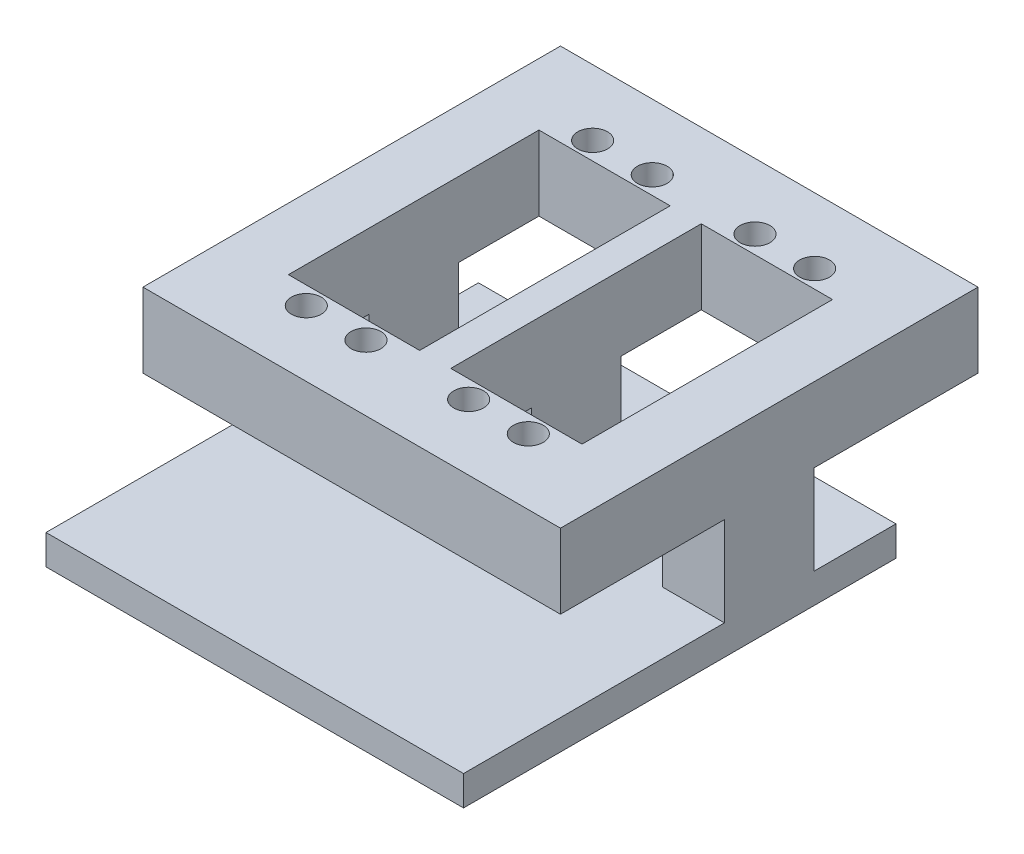
SolidWorks part; units mm, degrees
ref_plane "Front Plane" through (0, 0, 0) normal (0, 0, 1) x (1, 0, 0)
ref_plane "Top Plane" through (0, 0, 0) normal (0, 1, 0) x (1, 0, 0)
ref_plane "Right Plane" through (0, 0, 0) normal (1, 0, 0) x (0, 0, -1)
sketch "Sketch1" plane through (0, 0, 0) normal (0, 1, 0) x (1, 0, 0)
  line L0 (0, 74.7873) -> (0, -69.1899) construction
  line L1 (-35, 35) -> (35, 35)
  line L2 (-35, 35) -> (-35, -35)
  line L3 (-35, -35) -> (35, -35)
  line L4 (35, 35) -> (35, -35)
  line L5 (-35, 35) -> (35, -35) construction
  line L6 (-35, -35) -> (35, 35) construction
  line L7 (-24.6085, 21) -> (-2.6085, 21)
  line L8 (-24.6085, 21) -> (-24.6085, -21)
  line L9 (-24.6085, -21) -> (-2.6085, -21)
  line L10 (-2.6085, 21) -> (-2.6085, -21)
  line L11 (-24.6085, 21) -> (-2.6085, -21) construction
  line L12 (-24.6085, -21) -> (-2.6085, 21) construction
  line L13 (-120.0494, 0) -> (109.3545, 0) construction
  line L14 (35, 35) -> (-35, -35) construction
  line L15 (24.6085, -21) -> (2.6085, -21)
  line L16 (2.6085, 21) -> (2.6085, -21)
  line L17 (24.6085, 21) -> (2.6085, 21)
  line L18 (24.6085, 21) -> (24.6085, -21)
  circle A0 centre (-18.6085, 24) radius 2.5
  circle A1 centre (-8.6085, 24) radius 2.5
  circle A2 centre (-8.6085, -24) radius 2.5
  circle A3 centre (-18.6085, -24) radius 2.5
  circle A4 centre (8.6085, -24) radius 2.5
  circle A5 centre (18.6085, -24) radius 2.5
  circle A6 centre (8.6085, 24) radius 2.5
  circle A7 centre (18.6085, 24) radius 2.5
  point P0 (0, 0)
  point P6 (-13.6085, 0)
  dimension "D6" = 5
  dimension "D7" = 5
  dimension "D1" = 70
  dimension "D2" = 70
  dimension "D3" = 22
  dimension "D4" = 42
  dimension "D5" = 0
  dimension "D8" = 10
  dimension "D9" = 24
  dimension "D10" = 24
  dimension "D11" = 6
extrude "Boss-Extrude1" add sketch "Sketch1" along normal blind 12.5
sketch "Sketch3" plane through (0, 0, 0) normal (0, -1, 0) x (1, 0, 0)
  line L0 (-35, -35) -> (-35, 35) construction
  line L1 (-35, 7.5) -> (35, 7.5)
  line L2 (-35, 7.5) -> (-35, -7.5)
  line L3 (-35, -7.5) -> (35, -7.5)
  line L4 (35, 7.5) -> (35, -7.5)
  line L5 (35, 35) -> (35, -35) construction
  line L6 (-35, 35) -> (35, 35) construction
  line L7 (-24.6085, -21) -> (-24.6085, 21) construction
  line L8 (-35, 7.5) -> (-24.6085, 7.5)
  line L9 (-35, 7.5) -> (-35, -7.5)
  line L10 (-35, -7.5) -> (-24.6085, -7.5)
  line L11 (-24.6085, 7.5) -> (-24.6085, -7.5)
  line L12 (-2.6085, 21) -> (-2.6085, -21) construction
  line L13 (-2.6085, 7.5) -> (2.6085, 7.5)
  line L14 (-2.6085, 7.5) -> (-2.6085, -7.5)
  line L15 (-2.6085, -7.5) -> (2.6085, -7.5)
  line L16 (2.6085, 7.5) -> (2.6085, -7.5)
  line L17 (2.6085, -21) -> (2.6085, 21) construction
  line L18 (24.6085, 21) -> (24.6085, -21) construction
  line L19 (24.6085, 7.5) -> (35, 7.5)
  line L20 (24.6085, 7.5) -> (24.6085, -7.5)
  line L21 (24.6085, -7.5) -> (35, -7.5)
  line L22 (35, 7.5) -> (35, -7.5)
  dimension "D1" = 15
  dimension "D2" = 27.5
extrude "Boss-Extrude2" add sketch "Sketch3" along normal blind 15 contours L9 L8 L11 L10 | L14 L13 L16 L15 | L20 L19 L22 L21
sketch "Sketch8" plane through (0, -15, 0) normal (0, -1, 0) x (1, 0, 0)
  line L0 (35, -7.5) -> (35, -35) construction
  line L1 (-35, 21.25) -> (35, 21.25)
  line L2 (-35, 21.25) -> (-35, -21.25)
  line L3 (-35, -21.25) -> (35, -21.25)
  line L4 (35, 21.25) -> (35, -21.25)
  line L5 (-35, 21.25) -> (35, -21.25) construction
  line L6 (-35, -21.25) -> (35, 21.25) construction
  point P0 (0, 0)
extrude "Boss-Extrude5" add sketch "Sketch8" along normal blind 5
sketch "Sketch12" plane through (0, 0, 21.25) normal (0, 0, 1) x (1, 0, 0)
  line L1 (-35, -15) -> (35, -15)
  line L2 (-35, -15) -> (-35, -20)
  line L3 (-35, -20) -> (35, -20)
  line L4 (35, -15) -> (35, -20)
extrude "Boss-Extrude6" add sketch "Sketch12" along normal blind 30
